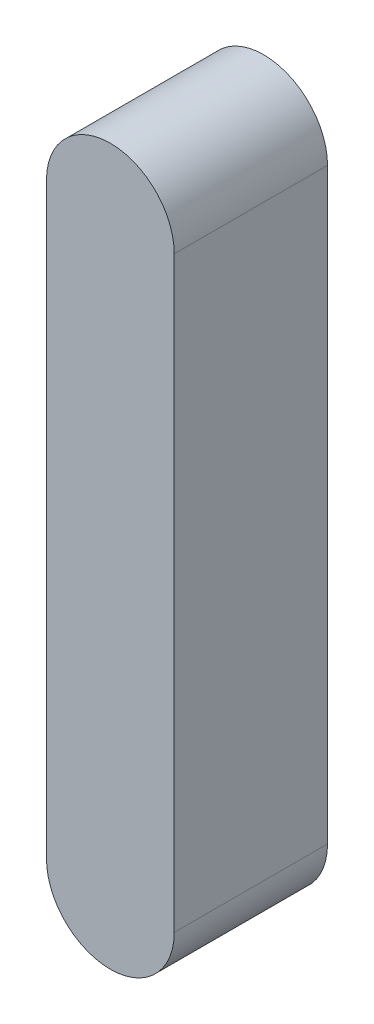
SolidWorks part; units mm, degrees
ref_plane "前视基准面" through (0, 0, 0) normal (0, 0, 1) x (1, 0, 0)
ref_plane "上视基准面" through (0, 0, 0) normal (0, 1, 0) x (1, 0, 0)
ref_plane "右视基准面" through (0, 0, 0) normal (1, 0, 0) x (0, 0, -1)
other "Configuration Table"
sketch "草图1" plane through (0, 0, 0) normal (0, 0, 1) x (1, 0, 0)
  line L0 (0, 0) -> (0, 115) construction
  line L1 (-12.5, 0) -> (-12.5, 115)
  line L2 (12.5, 0) -> (12.5, 115)
  arc A0 (-12.5, 0) -> (12.5, 0) centre (0, 0) ccw
  arc A1 (12.5, 115) -> (-12.5, 115) centre (0, 115) ccw
  point P3 (0, 57.5)
  dimension "D1" = 115
  dimension "D2" = 25
extrude "凸台-拉伸1" add sketch "草图1" along normal mid plane 30
